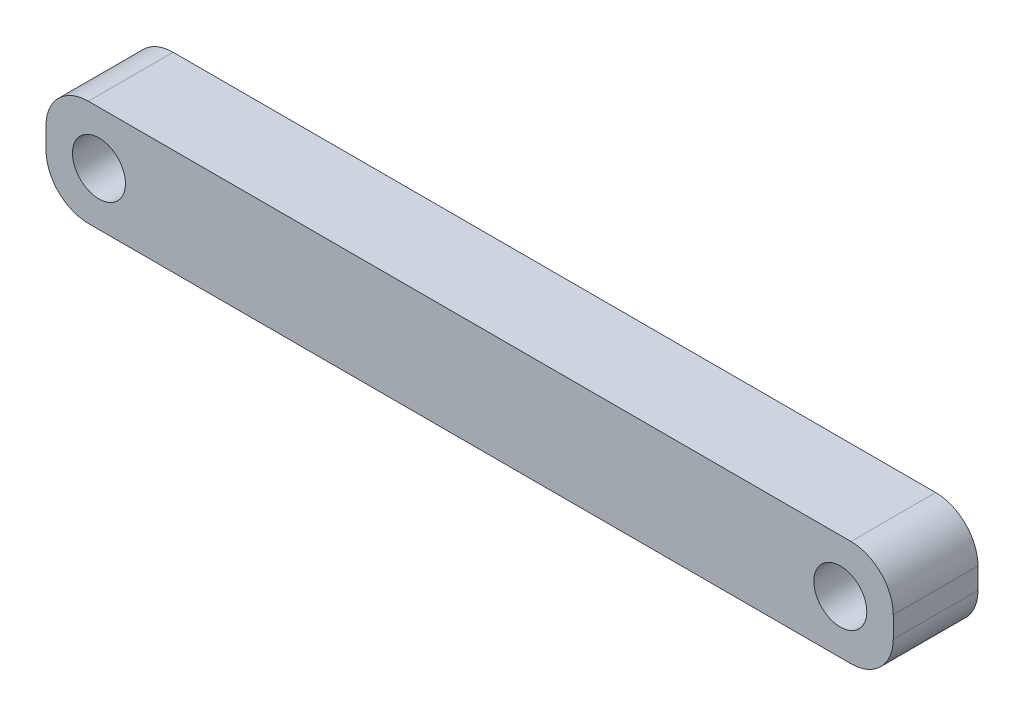
SolidWorks part; units mm, degrees
ref_plane "Front Plane" through (0, 0, 0) normal (0, 0, 1) x (1, 0, 0)
ref_plane "Top Plane" through (0, 0, 0) normal (0, 1, 0) x (1, 0, 0)
ref_plane "Right Plane" through (0, 0, 0) normal (1, 0, 0) x (0, 0, -1)
sketch "Sketch1" plane through (0, 0, 0) normal (0, 0, 1) x (1, 0, 0)
  line L1 (-40, -5) -> (40, -5)
  line L2 (-40, -5) -> (-40, 5)
  line L3 (-40, 5) -> (40, 5)
  line L4 (40, -5) -> (40, 5)
  line L5 (-40, -5) -> (40, 5) construction
  line L6 (-40, 5) -> (40, -5) construction
  circle A0 centre (-35, 0) radius 2.5
  circle A1 centre (35, 0) radius 2.5
  point P0 (0, 0)
  dimension "D3" = 5
  dimension "D4" = 5
  dimension "D6" = 5
  dimension "D7" = 5
  dimension "D8" = 5
  dimension "D1" = 80
  dimension "D2" = 10
  dimension "D5" = 5
extrude "Boss-Extrude1" add sketch "Sketch1" along normal blind 8
fillet "Fillet1" radius 4 4 edges at (40, -5, 4) (40, 5, 4) (-40, -5, 4) (-40, 5, 4)
